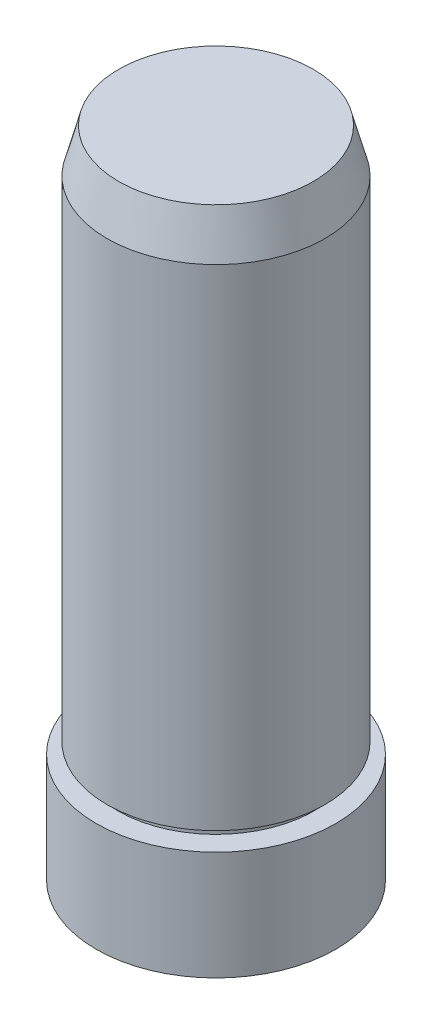
SolidWorks part; units mm, degrees
ref_plane "Спереди" through (0, 0, 0) normal (0, 0, 1) x (1, 0, 0)
ref_plane "Сверху" through (0, 0, 0) normal (0, 1, 0) x (1, 0, 0)
ref_plane "Справа" through (0, 0, 0) normal (1, 0, 0) x (0, 0, -1)
sketch "Эскиз1" plane through (0, 0, 0) normal (0, 1, 0) x (1, 0, 0)
  circle A0 centre (0, 0) radius 10
  dimension "D1" = 20
extrude "Бобышка-Вытянуть1" add sketch "Эскиз1" along normal blind 50
sketch "Эскиз2" plane through (0, 0, 0) normal (0, -1, 0) x (1, 0, 0)
  circle A0 centre (0, 0) radius 11
  dimension "D1" = 22
extrude "Бобышка-Вытянуть2" add sketch "Эскиз2" along normal blind 10
chamfer "Фаска1" distance 4 angle 15 1 edges at (0, 50, 10)
sketch "Эскиз3" plane through (0, 0, 0) normal (0, 1, 0) x (1, 0, 0)
  circle A0 centre (0, 0) radius 10 construction
  circle A1 centre (0, 0) radius 10
  circle A2 centre (0, 0) radius 9
  dimension "D1" = 1
extrude "Вырез-Вытянуть1" cut sketch "Эскиз3" along normal blind 1
ref_plane "___mouting_plane___" through (0, 0, 10) normal (0, 0, 1) x (1, 0, 0)
equation "\"H\"=10"
equation "\"D\"=20"
equation "\"L\"=50"
equation "\"D1@Эскиз1\" = \"D\""
equation "\"D1@Эскиз2\" = 1.1*\"D\""
equation "\"D1@Бобышка-Вытянуть1\"=\"L\""
equation "\"D1@Бобышка-Вытянуть2\"=\"H\""
